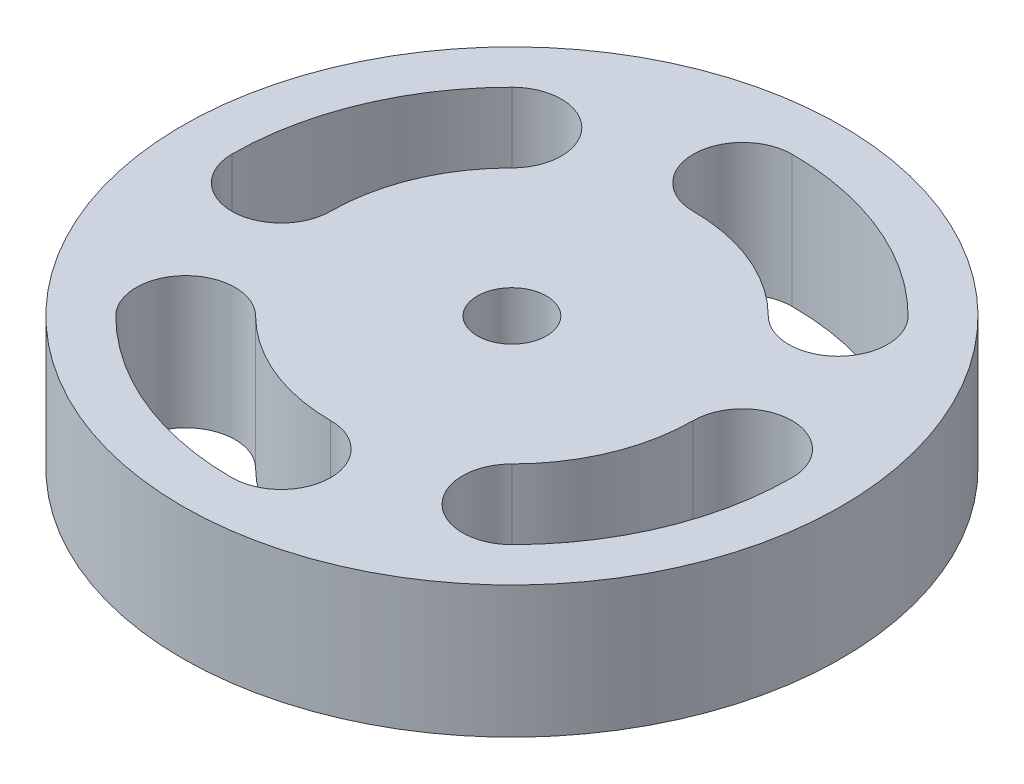
SolidWorks part; units mm, degrees
ref_plane "前视基准面" through (0, 0, 0) normal (0, 0, 1) x (1, 0, 0)
ref_plane "上视基准面" through (0, 0, 0) normal (0, 1, 0) x (1, 0, 0)
ref_plane "右视基准面" through (0, 0, 0) normal (1, 0, 0) x (0, 0, -1)
other "Configuration Table"
sketch "草图1" plane through (0, 0, 0) normal (0, 1, 0) x (1, 0, 0)
  circle A0 centre (0, 0) radius 50
  dimension "D1" = 100
extrude "凸台-拉伸1" add sketch "草图1" along normal blind 20
sketch "草图2" plane through (0, 20, 0) normal (0, 1, 0) x (1, 0, 0)
  circle A0 centre (0, 0) radius 5.25
  dimension "D1" = 10.5
extrude "切除-拉伸1" cut sketch "草图2" against normal blind 20
sketch "草图3" plane through (0, 20, 0) normal (0, 1, 0) x (1, 0, 0)
  line L0 (-1000, 0) -> (49000, 0) construction
  line L1 (0, -1000) -> (0, 49000) construction
  circle A0 centre (0, 0) radius 35
  circle A1 centre (0, 35) radius 7.5
  circle A2 centre (24.7487, 24.7487) radius 7.5
  circle A3 centre (35, 0) radius 7.5
  circle A4 centre (24.7487, -24.7487) radius 7.5
  circle A5 centre (0, -35) radius 7.5
  circle A6 centre (-24.7487, -24.7487) radius 7.5
  circle A7 centre (-35, 0) radius 7.5
  circle A8 centre (-24.7487, 24.7487) radius 7.5
  circle A9 centre (0, 0) radius 42.5
  circle A10 centre (0, 0) radius 27.5
  point P28 (0, 0)
  dimension "D1" = 70
  dimension "D2" = 15
  dimension "D3" = 8
extrude "切除-拉伸2" cut sketch "草图3" against normal blind 20 contours A10 A8 A0 A7 | A8 A9 A7 A0 | A0 A7 | A0 A7 | A0 A8 | A0 A8 | A0 A6 | A0 A6 | A6 A9 A5 A0 | A10 A6 A0 A5 | A0 A5 | A0 A5 | A0 A4 | A0 A4 | A4 A9 A3 A0 | A10 A4 A0 A3 | A0 A3 | A0 A3 | A0 A2 | A0 A2 | A10 A2 A0 A1 | A2 A9 A1 A0 | A0 A1 | A0 A1
